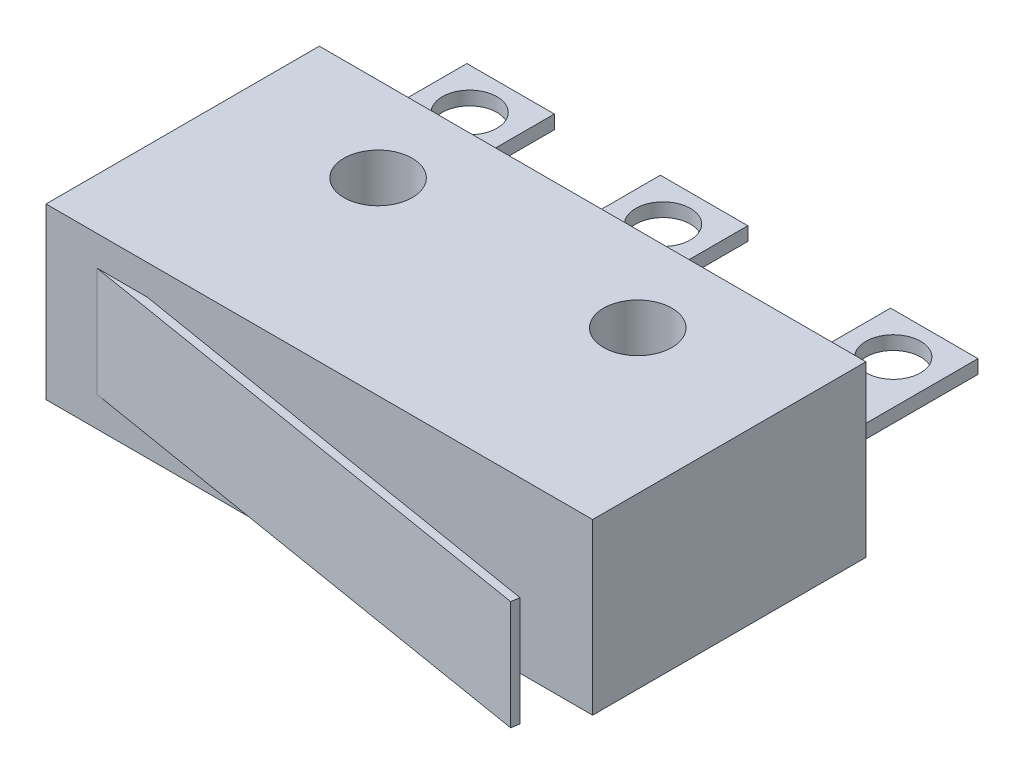
SolidWorks part; units mm, degrees
ref_plane "Front Plane" through (0, 0, 0) normal (0, 0, 1) x (1, 0, 0)
ref_plane "Top Plane" through (0, 0, 0) normal (0, 1, 0) x (1, 0, 0)
ref_plane "Right Plane" through (0, 0, 0) normal (1, 0, 0) x (0, 0, -1)
sketch "Sketch1" plane through (0, 0, 0) normal (0, 1, 0) x (1, 0, 0)
  line L1 (-10, 5) -> (10, 5)
  line L2 (-10, 5) -> (-10, -5)
  line L3 (-10, -5) -> (10, -5)
  line L4 (10, 5) -> (10, -5)
  line L5 (-10, 5) -> (10, -5) construction
  line L6 (-10, -5) -> (10, 5) construction
  point P0 (0, 0)
  dimension "D1" = 10
  dimension "D2" = 20
extrude "Boss-Extrude1" add sketch "Sketch1" along normal mid plane 6.2
sketch "Sketch3" plane through (0, 0, 0) normal (0, 1, 0) x (1, 0, 0)
  line L0 (-8.1393, -5) -> (10, -8)
  line L1 (-10, -5) -> (10, -5) construction
  line L2 (10, -8) -> (10.049, -7.704)
  line L3 (10.049, -7.704) -> (-6.3007, -5)
  line L4 (-6.3007, -5) -> (-8.1393, -5)
  dimension "D1" = 3
  dimension "D2" = 0.3
extrude "Boss-Extrude3" add sketch "Sketch3" along normal mid plane 4
sketch "Sketch4" plane through (0, 0, -5) normal (0, 0, -1) x (-1, 0, 0)
  line L0 (-11.3494, 0) -> (13.1934, 0) construction
  line L1 (-7.5, 4.0959) -> (-7.5, -5.2708) construction
  line L2 (1, 4.8139) -> (1, -7.2943) construction
  line L3 (8, 4.3896) -> (8, -6.8048) construction
  line L4 (-10, 3.1) -> (-10, -3.1) construction
  line L5 (10, 3.1) -> (10, -3.1) construction
  line L7 (-9.1, 0.25) -> (-5.9, 0.25)
  line L8 (-9.1, 0.25) -> (-9.1, -0.25)
  line L9 (-9.1, -0.25) -> (-5.9, -0.25)
  line L10 (-5.9, 0.25) -> (-5.9, -0.25)
  line L11 (-9.1, 0.25) -> (-5.9, -0.25) construction
  line L12 (-9.1, -0.25) -> (-5.9, 0.25) construction
  line L13 (-0.678, 0.25) -> (2.522, 0.25)
  line L14 (-0.678, 0.25) -> (-0.678, -0.25)
  line L15 (-0.678, -0.25) -> (2.522, -0.25)
  line L16 (2.522, 0.25) -> (2.522, -0.25)
  line L17 (-0.678, 0.25) -> (2.522, -0.25) construction
  line L18 (-0.678, -0.25) -> (2.522, 0.25) construction
  line L19 (6.4, 0.25) -> (9.6, 0.25)
  line L20 (6.4, 0.25) -> (6.4, -0.25)
  line L21 (6.4, -0.25) -> (9.6, -0.25)
  line L22 (9.6, 0.25) -> (9.6, -0.25)
  line L23 (6.4, 0.25) -> (9.6, -0.25) construction
  line L24 (6.4, -0.25) -> (9.6, 0.25) construction
  point P13 (-7.5, 0)
  point P14 (1, 0)
  point P15 (8, 0)
  point P16 (0.922, 0)
  point P19 (-7.5, 0)
  point P26 (8, 0)
  dimension "D1" = 2.5
  dimension "D2" = 2
  dimension "D3" = 9
  dimension "D4" = 3.2
  dimension "D5" = 3.2
  dimension "D6" = 3.2
  dimension "D7" = 0.5
  dimension "D8" = 0.5
  dimension "D9" = 0.5
extrude "Boss-Extrude4" add sketch "Sketch4" along normal blind 5
sketch "Sketch7" plane through (0, 0.25, 0) normal (0, 1, 0) x (1, 0, 0)
  line L0 (-11.8792, 8.5) -> (12.2012, 8.5) construction
  line L1 (-8, 10) -> (-8, 6.4877) construction
  line L2 (-9.6, 10) -> (-6.4, 10) construction
  line L3 (-0.922, 10) -> (-0.922, 6.9245) construction
  line L4 (-2.522, 10) -> (0.678, 10) construction
  line L5 (7.5, 10) -> (7.5, 6.4877) construction
  line L6 (5.9, 10) -> (9.1, 10) construction
  circle A0 centre (-8, 8.5) radius 1
  circle A1 centre (-0.922, 8.5) radius 1
  circle A2 centre (7.5, 8.5) radius 1
  point P14 (-8, 8.5)
  point P15 (-0.922, 8.5)
  point P16 (7.5, 8.5)
  dimension "D2" = 2
  dimension "D1" = 1.5
extrude "Cut-Extrude1" cut sketch "Sketch7" against normal blind 5
sketch "Sketch8" plane through (0, 3.1, 0) normal (0, 1, 0) x (1, 0, 0)
  line L0 (-12.6212, 1.9) -> (13.6729, 1.9) construction
  line L1 (10, 5) -> (-10, 5) construction
  line L2 (10, -5) -> (10, 5) construction
  line L3 (-10, 5) -> (-10, -5) construction
  circle A0 centre (-4.75, 1.9) radius 1.25
  circle A1 centre (4.75, 1.9) radius 1.25
  point P12 (0, 0)
  dimension "D2" = 2.5
  dimension "D3" = 2.5
  dimension "D1" = 3.1
  dimension "D4" = 5.25
  dimension "D5" = 5.25
extrude "Cut-Extrude2" cut sketch "Sketch8" against normal through all
